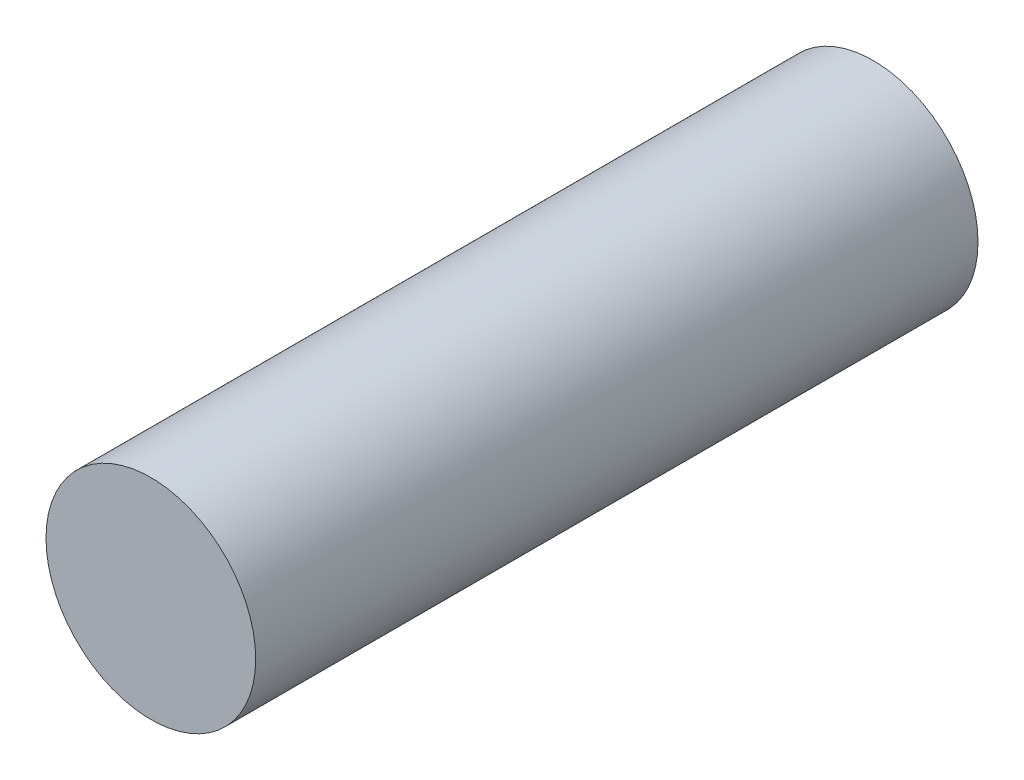
SolidWorks part; units mm, degrees
ref_plane "Front Plane" through (0, 0, 0) normal (0, 0, 1) x (1, 0, 0)
ref_plane "Top Plane" through (0, 0, 0) normal (0, 1, 0) x (1, 0, 0)
ref_plane "Right Plane" through (0, 0, 0) normal (1, 0, 0) x (0, 0, -1)
sketch "Sketch1" plane through (0, 0, 0) normal (0, 0, 1) x (1, 0, 0)
  circle A0 centre (-4.4097, 2.9322) radius 4.5
  dimension "D1" = 9
extrude "Boss-Extrude1" add sketch "Sketch1" along normal blind 31
